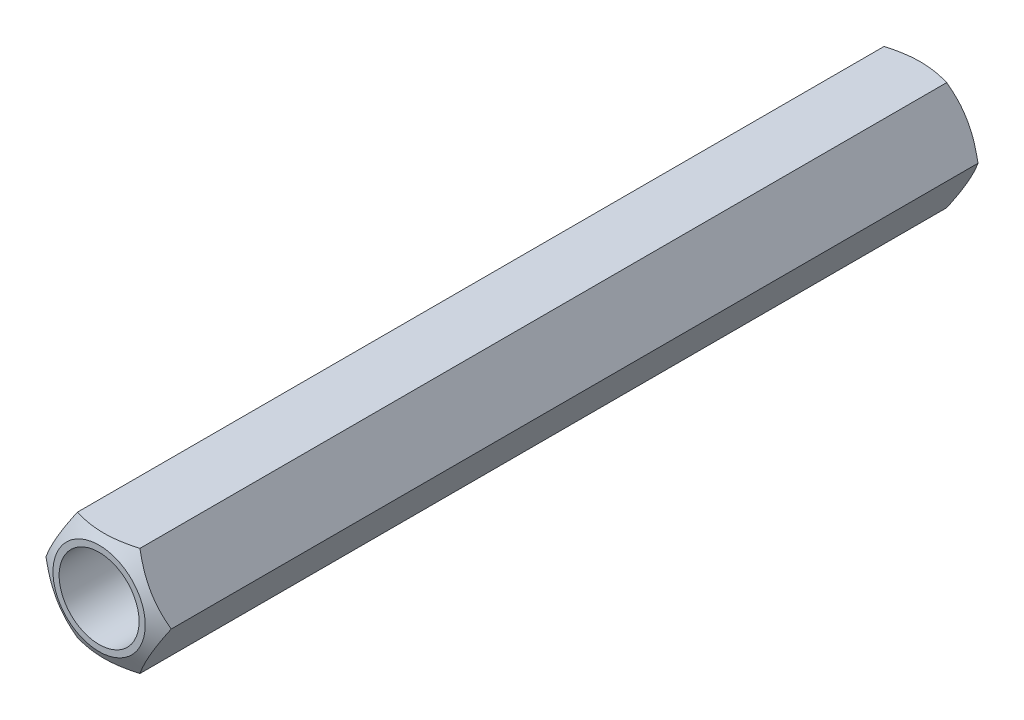
SolidWorks part; units mm, degrees
material "高铅黄铜，UNS C34200"
ref_plane "前视基准面" through (0, 0, 0) normal (0, 0, 1) x (1, 0, 0)
ref_plane "上视基准面" through (0, 0, 0) normal (0, 1, 0) x (1, 0, 0)
ref_plane "右视基准面" through (0, 0, 0) normal (1, 0, 0) x (0, 0, -1)
sketch "草图1" plane through (0, 0, 0) normal (0, 0, 1) x (1, 0, 0)
  line L0 (0, 0) -> (2.573, 0) construction
  line L2 (2.35, 0) -> (1.175, 2.0352)
  line L3 (1.175, 2.0352) -> (-1.175, 2.0352)
  line L4 (-1.175, 2.0352) -> (-2.35, 0)
  line L5 (-2.35, 0) -> (-1.175, -2.0352)
  line L6 (-1.175, -2.0352) -> (1.175, -2.0352)
  line L7 (1.175, -2.0352) -> (2.35, 0)
  circle A0 centre (0, 0) radius 1.5
  circle A1 centre (0, 0) radius 2.0352 construction
  point P3 (2.35, 0)
  dimension "D1" = 3
  dimension "D2" = 4.7
extrude "凸台-拉伸1" add sketch "草图1" along normal blind 31 contours A0 | L2 L3 L4 L5 L6 L7
sketch "草图2" plane through (0, 0, 0) normal (0, 1, 0) x (1, 0, 0)
  line L0 (0, 0) -> (0, 4.8983) construction
  line L1 (0, 1) -> (2.35, -0.3568)
  line L2 (2.35, -31) -> (2.35, 0) construction
  line L3 (2.35, -0.3568) -> (2.35, 2.6869)
  line L4 (2.35, 2.6869) -> (0, 2.6869)
  line L5 (0, 2.6869) -> (0, 1)
  line L6 (1.175, 0) -> (-1.175, 0) construction
  point P8 (2.35, -0.4966)
  dimension "D1" = 60
  dimension "D2" = 1
revolve "切除-旋转1" cut sketch "草图2" angle 360 about L0
ref_plane "基准面4" through (0, 0, 15.5) normal (0, 0, -1) x (-1, 0, 0)
mirror "镜向1" about plane through (0, 0, 15.5) normal (0, 0, -1) of "切除-旋转1"
